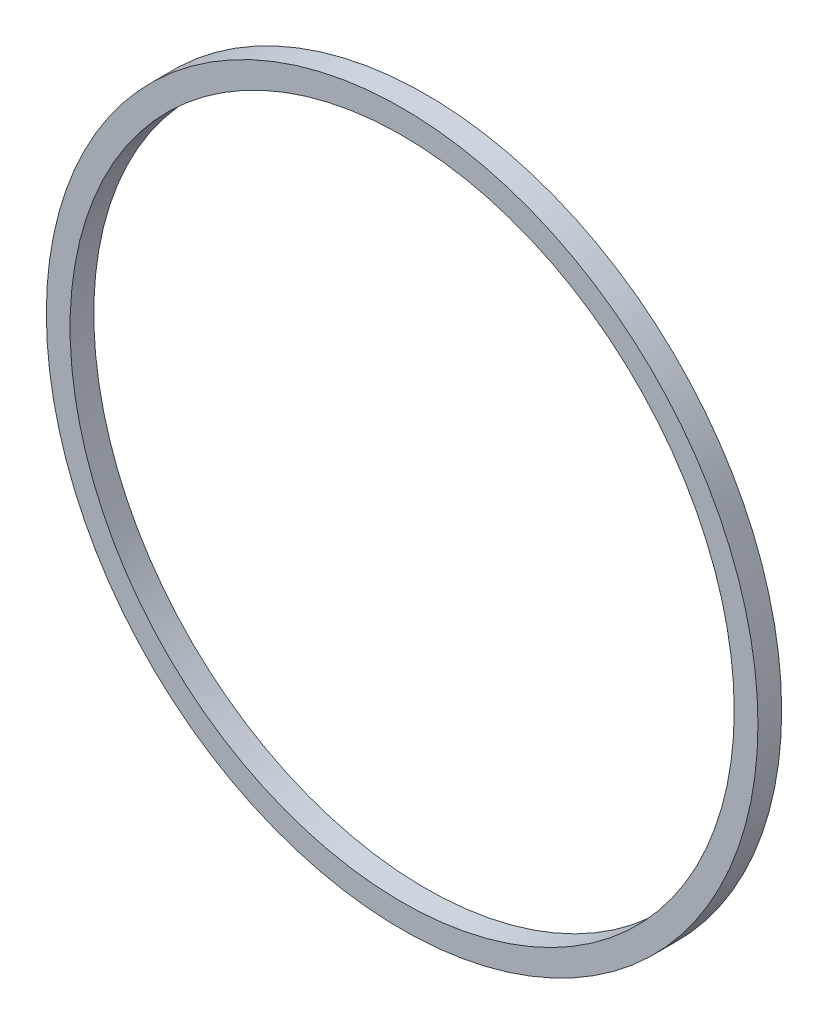
SolidWorks part; units mm, degrees
ref_plane "前视基准面" through (0, 0, 0) normal (0, 0, 1) x (1, 0, 0)
ref_plane "上视基准面" through (0, 0, 0) normal (0, 1, 0) x (1, 0, 0)
ref_plane "右视基准面" through (0, 0, 0) normal (1, 0, 0) x (0, 0, -1)
sketch "草图1" plane through (0, 0, 0) normal (0, 0, 1) x (1, 0, 0)
  circle A0 centre (0, 0) radius 30
  circle A1 centre (0, 0) radius 28
extrude "凸台-拉伸1" add sketch "草图1" along normal blind 2
